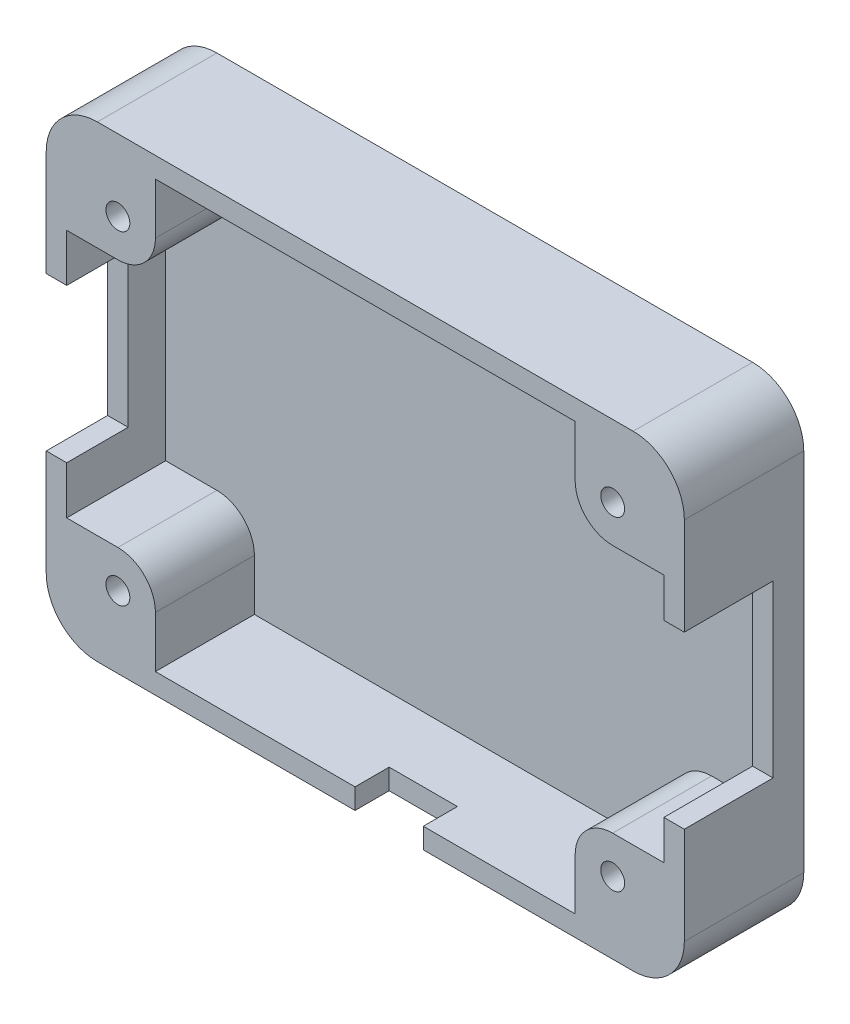
SolidWorks part; units mm, degrees
ref_plane "前视基准面" through (0, 0, 0) normal (0, 0, 1) x (1, 0, 0)
ref_plane "上视基准面" through (0, 0, 0) normal (0, 1, 0) x (1, 0, 0)
ref_plane "右视基准面" through (0, 0, 0) normal (1, 0, 0) x (0, 0, -1)
sketch "草图1" plane through (0, 0, 0) normal (0, 0, 1) x (1, 0, 0)
  line L1 (-18.7, 13.7) -> (18.7, 13.7)
  line L2 (-18.7, 13.7) -> (-18.7, -13.7)
  line L3 (-18.7, -13.7) -> (18.7, -13.7)
  line L4 (18.7, 13.7) -> (18.7, -13.7)
  line L5 (-18.7, 13.7) -> (18.7, -13.7) construction
  line L6 (-18.7, -13.7) -> (18.7, 13.7) construction
  point P0 (0, 0)
  dimension "D1" = 27.4
  dimension "D2" = 37.4
extrude "凸台-拉伸1" add sketch "草图1" along normal blind 7
shell "抽壳1" thickness 1.2
sketch "草图3" plane through (0, 0, 7) normal (0, 0, 1) x (1, 0, 0)
  line L1 (-19.0287, -4.5) -> (-17.0287, -4.5)
  line L2 (-19.0287, -4.5) -> (-19.0287, 4.5)
  line L3 (-19.0287, 4.5) -> (-17.0287, 4.5)
  line L4 (-17.0287, -4.5) -> (-17.0287, 4.5)
  line L5 (-19.0287, -4.5) -> (-17.0287, 4.5) construction
  line L6 (-19.0287, 4.5) -> (-17.0287, -4.5) construction
  point P0 (-18.0287, 0)
  dimension "D1" = 9
  dimension "D2" = 0
  dimension "D3" = 2
  dimension "D4" = 18.0287
extrude "切除-拉伸1" cut sketch "草图3" against normal blind 3.6
sketch "草图4" plane through (0, 0, 7) normal (0, 0, 1) x (1, 0, 0)
  line L0 (18.7, 13.7) -> (-18.7, 13.7) construction
  line L1 (17.189, -5) -> (19.189, -5)
  line L2 (17.189, -5) -> (17.189, 5)
  line L3 (17.189, 5) -> (19.189, 5)
  line L4 (19.189, -5) -> (19.189, 5)
  line L5 (17.189, -5) -> (19.189, 5) construction
  line L6 (17.189, 5) -> (19.189, -5) construction
  point P0 (18.189, 0)
  dimension "D1" = 18.189
  dimension "D2" = 2
  dimension "D3" = 10
  dimension "D4" = 13.7
extrude "切除-拉伸2" cut sketch "草图4" against normal blind 5.2
sketch "草图5" plane through (0, 0, 7) normal (0, 0, 1) x (1, 0, 0)
  line L0 (17.5, -12.5) -> (17.5, -5) construction
  line L1 (-0.6, -14.133) -> (3.4, -14.133)
  line L2 (-0.6, -14.133) -> (-0.6, -12.133)
  line L3 (-0.6, -12.133) -> (3.4, -12.133)
  line L4 (3.4, -14.133) -> (3.4, -12.133)
  line L5 (-0.6, -14.133) -> (3.4, -12.133) construction
  line L6 (-0.6, -12.133) -> (3.4, -14.133) construction
  point P0 (1.4, -13.133)
  dimension "D1" = 2
  dimension "D2" = 4
  dimension "D3" = 16.1
  dimension "D4" = 13.133
extrude "切除-拉伸3" cut sketch "草图5" against normal blind 2
sketch "草图6" plane through (0, 0, 1.2) normal (0, 0, 1) x (1, 0, 0)
  line L0 (17.5, 0) -> (-21.3277, 0) construction
  line L1 (17.5, 5) -> (17.5, -5) construction
  line L2 (0, 0) -> (0, 16.902) construction
  line L3 (14.5, -7.3) -> (17.5, -7.3)
  line L4 (17.5, -12.5) -> (17.5, 12.5) construction
  line L5 (12.3, -9.5) -> (12.3, -12.5)
  line L6 (3.4, -12.5) -> (17.5, -12.5) construction
  line L7 (12.3, -12.5) -> (17.5, -12.5)
  line L8 (17.5, -12.5) -> (17.5, -7.3)
  line L9 (-12.3, -12.5) -> (-17.5, -12.5)
  line L10 (-12.3, -9.5) -> (-12.3, -12.5)
  line L11 (-14.5, -7.3) -> (-17.5, -7.3)
  line L12 (-17.5, -12.5) -> (-17.5, -7.3)
  line L13 (-17.5, 12.5) -> (-17.5, 7.3)
  line L14 (-14.5, 7.3) -> (-17.5, 7.3)
  line L15 (-12.3, 9.5) -> (-12.3, 12.5)
  line L16 (-12.3, 12.5) -> (-17.5, 12.5)
  line L17 (17.5, 12.5) -> (17.5, 7.3)
  line L18 (12.3, 12.5) -> (17.5, 12.5)
  line L19 (12.3, 9.5) -> (12.3, 12.5)
  line L20 (14.5, 7.3) -> (17.5, 7.3)
  arc A0 (14.5, -7.3) -> (12.3, -9.5) centre (14.5, -9.5) ccw
  circle A1 centre (14.5, -9.5) radius 0.7
  circle A2 centre (-14.5, -9.5) radius 0.7
  arc A3 (-14.5, -7.3) -> (-12.3, -9.5) centre (-14.5, -9.5) cw
  arc A4 (-14.5, 7.3) -> (-12.3, 9.5) centre (-14.5, 9.5) ccw
  circle A5 centre (-14.5, 9.5) radius 0.7
  circle A6 centre (14.5, 9.5) radius 0.7
  arc A7 (14.5, 7.3) -> (12.3, 9.5) centre (14.5, 9.5) cw
  dimension "D1" = 4.4
  dimension "D3" = 1.4
  dimension "D2" = 5.2
  dimension "D4" = 5.2
extrude "凸台-拉伸2" add sketch "草图6" along normal up to surface (5.8 mm away) up to face at (13.2, -10.4, 7)
fillet "圆角1" radius 3 4 edges at (-18.7, -13.7, 3.5) (-18.7, 13.7, 3.5) (18.7, 13.7, 3.5) (18.7, -13.7, 3.5)
